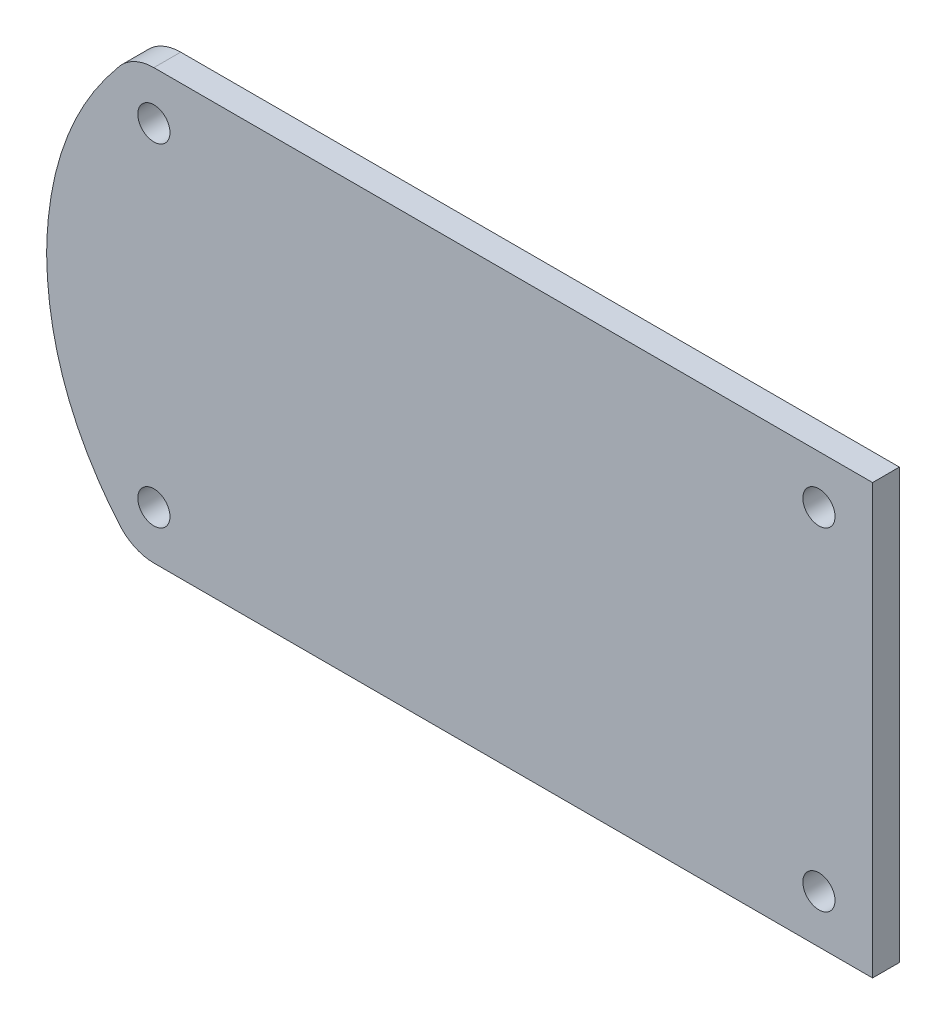
SolidWorks part; units mm, degrees
ref_plane "Alzado" through (0, 0, 0) normal (0, 0, 1) x (1, 0, 0)
ref_plane "Planta" through (0, 0, 0) normal (0, 1, 0) x (1, 0, 0)
ref_plane "Vista lateral" through (0, 0, 0) normal (1, 0, 0) x (0, 0, -1)
sketch "Croquis1" plane through (0, 0, 0) normal (0, 0, 1) x (1, 0, 0)
  line L0 (-29.5025, -44.95) -> (-23.1778, -37.2438)
  line L1 (29.5025, 44.95) -> (23.1778, 37.2438)
  line L2 (-10.5003, 28.196) -> (10.5003, 28.196)
  line L3 (10.4997, -24.196) -> (-10.5003, -24.196)
  line L4 (10.4997, 24.196) -> (-10.5003, 24.196)
  line L5 (23.1779, -37.2437) -> (29.5025, -44.95)
  line L6 (41.9317, 35.7196) -> (21.7292, 5.5661)
  line L7 (-10.5003, -28.196) -> (10.4997, -28.196)
  line L8 (-85.5141, -4.166) -> (-47.6698, -4.166)
  line L9 (-85.5141, 4.166) -> (-47.6698, 4.166)
  line L10 (-97.3181, -20) -> (-50.1355, -20)
  line L11 (-23.1779, 37.2437) -> (-29.5025, 44.95)
  line L12 (41.9317, -35.7196) -> (21.7292, -5.5661)
  line L13 (-97.3181, 20) -> (-50.1355, 20)
  line L14 (-10.5003, -26.196) -> (10.4997, -26.196)
  line L15 (-10.5003, 26.196) -> (10.4997, 26.196)
  arc A0 (21.7292, 5.5661) -> (21.7292, -5.5661) centre (30.037, 0) ccw
  circle A1 centre (-25.3716, 27.6416) radius 2.25
  arc A2 (41.9317, 35.7196) -> (29.5025, 44.95) centre (35.4932, 40.0333) ccw
  arc A3 (-41.8863, -35.6526) -> (-29.5025, -44.95) centre (-35.4932, -40.0333) ccw
  circle A4 centre (-35.4932, 40.0333) radius 2.25
  arc A5 (-41.8863, -35.6526) -> (-50.1355, -20) centre (-50.1355, -30) ccw
  circle A6 centre (-35.4932, -40.0333) radius 2.25
  arc A7 (14.0461, 28.0999) -> (23.1778, 37.2438) centre (-27.1528, 78.3757) ccw
  circle A8 centre (15.25, -15.25) radius 3
  arc A9 (-14.0461, 28.0999) -> (-11.8672, 27.8665) centre (-12.7784, 29.6469) ccw
  circle A10 centre (35.4932, -40.0333) radius 2.25
  arc A11 (14.0461, -28.0999) -> (11.8672, -27.8665) centre (12.7784, -29.6469) ccw
  circle A12 centre (-15.25, 15.25) radius 3
  arc A13 (10.4997, 24.196) -> (10.4997, 26.196) centre (10.4997, 25.196) ccw
  arc A14 (-47.6698, 4.166) -> (-46.6061, 8.9284) centre (-47.6698, 6.666) ccw
  circle A15 centre (-25.3716, -27.6416) radius 2.25
  arc A16 (-48.7757, -9.4863) -> (-46.6061, -8.9284) centre (-49.1589, -3.4986) ccw
  circle A17 centre (-35.3181, 15.5) radius 1.5
  arc A18 (-11.8672, -27.8665) -> (-10.5003, -28.196) centre (-10.5003, -25.196) ccw
  circle A19 centre (25.3716, -27.6416) radius 2.25
  arc A20 (-14.0461, -28.0999) -> (-23.1778, -37.2438) centre (27.1528, -78.3757) ccw
  arc A21 (29.5025, -44.95) -> (41.9317, -35.7196) centre (35.4932, -40.0333) ccw
  arc A22 (11.8672, 27.8665) -> (14.0461, 28.0999) centre (12.7784, 29.6469) ccw
  arc A23 (10.4997, -28.196) -> (11.8672, -27.8665) centre (10.5003, -25.196) ccw
  arc A24 (-10.5003, -24.196) -> (-10.5003, -26.196) centre (-10.5003, -25.196) ccw
  circle A25 centre (-15.25, -15.25) radius 3
  circle A26 centre (-97.3181, 15.5) radius 1.5
  arc A27 (-46.6061, -8.9284) -> (-47.6698, -4.166) centre (-47.6698, -6.666) ccw
  circle A28 centre (15.25, 15.25) radius 3
  arc A29 (-50.1355, 20) -> (-41.8863, 35.6526) centre (-50.1355, 30) ccw
  arc A30 (-11.8672, -27.8665) -> (-14.0461, -28.0999) centre (-12.7784, -29.6469) ccw
  circle A31 centre (-35.3181, -15.5) radius 1.5
  arc A32 (-10.5003, 26.196) -> (-10.5003, 24.196) centre (-10.5003, 25.196) ccw
  circle A33 centre (25.3716, 27.6416) radius 2.25
  arc A34 (-88.511, 7.03) -> (-85.5141, 4.166) centre (-85.5141, 7.166) ccw
  arc A35 (-88.511, -7.03) -> (-81.5427, -13.2223) centre (-82.5172, -7.302) ccw
  arc A36 (-10.5003, 28.196) -> (-11.8672, 27.8665) centre (-10.5003, 25.196) ccw
  circle A37 centre (-97.3181, -15.5) radius 1.5
  arc A38 (-97.3181, 20) -> (-100.6815, 18.3128) centre (-97.3181, 15.804) ccw
  arc A39 (-81.5427, 13.2223) -> (-48.7757, 9.4863) centre (-27.5409, 341.2912) ccw
  arc A40 (-81.5427, 13.2223) -> (-88.511, 7.03) centre (-82.5172, 7.302) ccw
  arc A41 (11.8672, 27.8665) -> (10.5003, 28.196) centre (10.5003, 25.196) ccw
  arc A42 (-48.7757, -9.4863) -> (-81.5427, -13.2223) centre (-27.5408, -341.2912) ccw
  arc A43 (-85.5141, -4.166) -> (-88.511, -7.03) centre (-85.5141, -7.166) ccw
  arc A44 (23.1779, -37.2437) -> (14.0461, -28.0999) centre (-27.1523, -78.3761) ccw
  circle A45 centre (35.4932, 40.0333) radius 2.25
  arc A46 (-46.6061, 8.9284) -> (-48.7757, 9.4863) centre (-49.1589, 3.4986) ccw
  arc A47 (10.4997, -26.196) -> (10.4997, -24.196) centre (10.4997, -25.196) ccw
  arc A48 (-29.5025, 44.95) -> (-41.8863, 35.6526) centre (-35.4932, 40.0333) ccw
  arc A49 (-23.1779, 37.2437) -> (-14.0461, 28.0999) centre (27.1523, 78.3761) ccw
  arc A50 (-100.6815, -18.3128) -> (-97.3181, -20) centre (-97.3181, -15.804) ccw
  spline S0 degree 3 poles (-107.3181, 0) (-107.2524, 7.0597) (-104.9757, 13.1646) (-100.6815, 18.3128) knots 0 0 0 0 1 1 1 1
  spline S1 degree 3 poles (-107.3181, 0) (-107.2524, -7.0597) (-104.9757, -13.1646) (-100.6815, -18.3128) knots 0 0 0 0 1 1 1 1
extrude "Saliente-Extruir1" add sketch "Croquis1" along normal blind 2.5
sketch "Croquis2" plane through (0, 0, 2.5) normal (0, 0, 1) x (1, 0, 0)
  line L9 (-50.1355, 20) -> (-30.3181, 20)
  line L10 (-30.3181, 20) -> (-30.3181, -20)
  line L11 (-97.3181, -20) -> (-50.1355, -20)
  line L12 (-50.1355, 20) -> (-97.3181, 20)
  line L13 (-97.3181, -20) -> (-50.1355, -20)
  line L14 (-50.1355, 20) -> (-97.3181, 20)
  line L15 (-30.3181, -20) -> (-50.1355, -20)
  circle A0 centre (-35.3181, 15.5) radius 1.5
  circle A1 centre (-35.3181, -15.5) radius 1.5
  circle A2 centre (-97.3181, -15.5) radius 1.5
  circle A3 centre (-97.3181, 15.5) radius 1.5
  arc A15 (-100.6815, -18.3128) -> (-97.3181, -20) centre (-97.3181, -15.804) ccw
  arc A16 (-97.3181, 20) -> (-100.6815, 18.3128) centre (-97.3181, 15.804) ccw
  arc A17 (-100.6815, -18.3128) -> (-97.3181, -20) centre (-97.3181, -15.804) ccw
  arc A18 (-97.3181, 20) -> (-100.6815, 18.3128) centre (-97.3181, 15.804) ccw
  spline S10 degree 3 poles (2650.3508, 1146.8217) (-3516.1587, -706.4287) (2954.9396, -417.2363) (442.3563, 2224.0498) knots -16.725775 -16.725775 -16.725775 -16.725775 31.440548 31.440548 31.440548 31.440548 only from (-107.3181, 0) to (-100.6815, -18.3128)
  spline S11 degree 3 poles (442.3285, -2224.079) (2954.9944, 417.2415) (-3516.2176, 706.4372) (2650.4025, -1146.8373) knots -30.440726 -30.440726 -30.440726 -30.440726 17.725909 17.725909 17.725909 17.725909 only from (-100.6815, 18.3128) to (-107.3181, 0)
  spline S12 degree 3 poles (-107.3181, 0) (-107.2524, -7.0597) (-104.9757, -13.1646) (-100.6815, -18.3128) knots 0 0 0 0 1 1 1 1
  spline S13 degree 3 poles (-100.6815, 18.3128) (-104.9757, 13.1646) (-107.2524, 7.0597) (-107.3181, 0) knots 0 0 0 0 1 1 1 1
  dimension "D2" = 5
  dimension "D1" = 0
sketch "Croquis3" plane through (0, 0, 2.5) normal (0, 0, 1) x (1, 0, 0)
  line L1 (-128.0112, 59.7951) -> (65.6374, 59.7951)
  line L2 (-128.0112, 59.7951) -> (-128.0112, -63.0948)
  line L3 (-128.0112, -63.0948) -> (65.6374, -63.0948)
  line L4 (65.6374, 59.7951) -> (65.6374, -63.0948)
extrude "Saliente-Extruir2" add sketch "Croquis2" along normal blind 2.5
extrude "Cortar-Extruir3" cut sketch "Croquis3" against normal up to vertex
